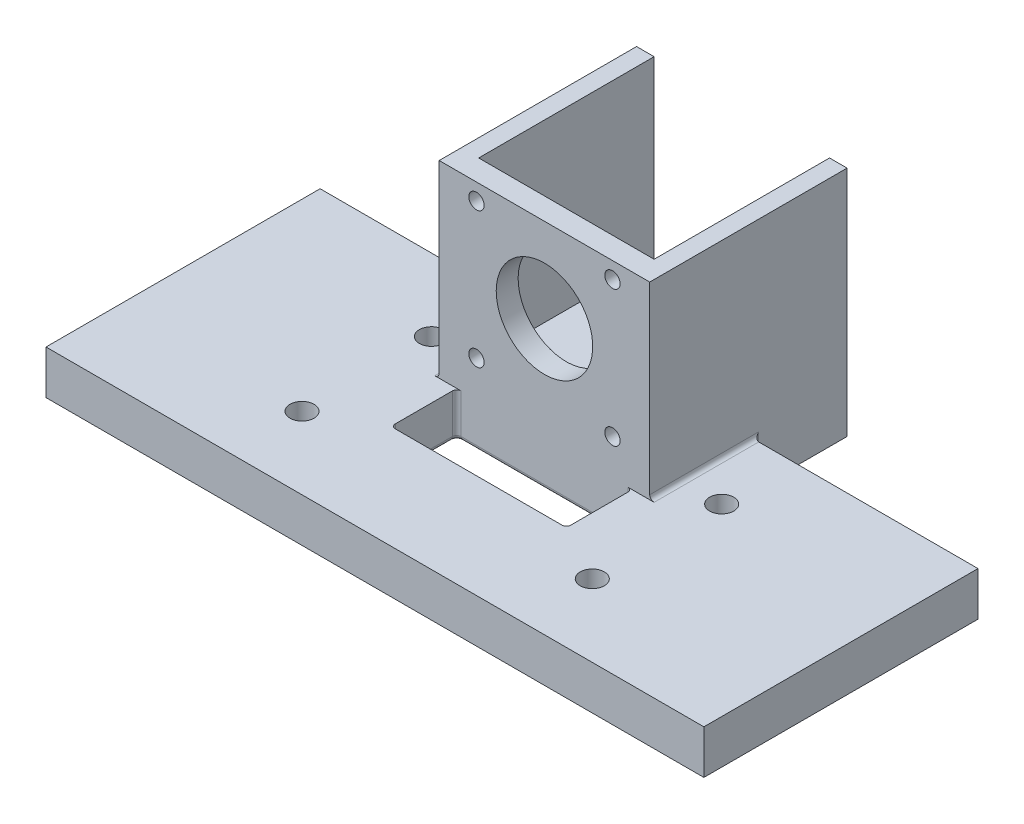
SolidWorks part; units mm, degrees
ref_plane "Front Plane" through (0, 0, 0) normal (0, 0, 1) x (1, 0, 0)
ref_plane "Top Plane" through (0, 0, 0) normal (0, 1, 0) x (1, 0, 0)
ref_plane "Right Plane" through (0, 0, 0) normal (1, 0, 0) x (0, 0, -1)
sketch "Sketch1" plane through (0, 0, 0) normal (0, 1, 0) x (1, 0, 0)
  line L0 (51, 62.5) -> (51, 83.65)
  line L1 (0, 0) -> (150, 0)
  line L2 (0, 0) -> (0, 62.5)
  line L4 (150, 0) -> (150, 62.5)
  line L5 (51, 83.65) -> (99, 83.65)
  line L6 (99, 83.65) -> (99, 62.5)
  line L8 (0, 62.5) -> (51, 62.5)
  line L9 (99, 62.5) -> (150, 62.5)
  line L10 (55, 38.65) -> (55, 23.65)
  line L11 (95, 38.65) -> (95, 23.65)
  line L14 (75, 83.65) -> (75, 38.65)
  line L15 (51, 83.65) -> (99, 83.65)
  line L17 (55, 23.65) -> (95, 23.65)
  line L22 (55, 38.65) -> (95, 38.65)
  circle A0 centre (108.0546, 46) radius 2.75
  circle A1 centre (41.8737, 46) radius 2.75
  circle A2 centre (41.8737, 16.5) radius 2.75
  circle A3 centre (108.0546, 16.5) radius 2.75
  dimension "D9" = 5.5
  dimension "D11" = 5.5
  dimension "D14" = 5.5
  dimension "D15" = 5.5
  dimension "D1" = 62.5
  dimension "D2" = 150
  dimension "D3" = 48
  dimension "D4" = 51
  dimension "D5" = 51
  dimension "D6" = 21.15
  dimension "D7" = 45
extrude "Boss-Extrude1" add sketch "Sketch1" along normal blind 10
sketch "Sketch3" plane through (0, 10, 0) normal (0, 1, 0) x (1, 0, 0)
  line L2 (95, 38.65) -> (95, 43.65)
  line L3 (55, 38.65) -> (95, 38.65)
  line L6 (95, 43.65) -> (55, 43.65)
  line L7 (95, 43.65) -> (95, 38.65)
  line L8 (95, 38.65) -> (55, 38.65)
  line L9 (55, 43.65) -> (55, 38.65)
  dimension "D3" = 40
extrude "Boss-Extrude2" add sketch "Sketch3" along normal blind 43 contours L6 L9 L3 L2
sketch "Sketch4" plane through (0, 0, -43.65) normal (0, 0, -1) x (-1, 0, 0)
  line L0 (-75, 53) -> (-75, 49.25)
  line L1 (-75, 49.25) -> (-75, 33.75)
  line L2 (-75, 22.75) -> (-75, 18.25)
  line L3 (-95, 53) -> (-55, 53) construction
  line L4 (-75, 49.25) -> (-90.5, 49.25)
  line L5 (-75, 49.25) -> (-59.5, 49.25)
  line L6 (-75, 18.25) -> (-90.5, 18.25)
  line L7 (-75, 18.25) -> (-59.5, 18.25)
  circle A0 centre (-90.5, 49.25) radius 1.75
  circle A1 centre (-59.5, 49.25) radius 1.75
  circle A2 centre (-75, 33.75) radius 11
  circle A3 centre (-90.5, 18.25) radius 1.75
  circle A4 centre (-59.5, 18.25) radius 1.75
  dimension "D4" = 3.5
  dimension "D5" = 3.5
  dimension "D7" = 22
  dimension "D9" = 3.5
  dimension "D10" = 3.5
  dimension "D1" = 3.75
  dimension "D2" = 15.5
  dimension "D3" = 15.5
  dimension "D6" = 15.5
  dimension "D8" = 4.5
extrude "Cut-Extrude1" cut sketch "Sketch4" against normal up to next
sketch "Sketch8" plane through (0, 10, 0) normal (0, 1, 0) x (1, 0, 0)
  line L2 (51, 83.65) -> (55, 83.65)
  line L7 (55, 38.65) -> (53.5, 38.65)
  line L8 (55, 43.65) -> (56.5, 43.65)
  line L12 (53.5, 38.65) -> (55, 38.65)
  line L14 (53.5, 83.65) -> (55, 83.65)
  line L16 (53.5, 38.65) -> (55, 38.65)
  line L18 (53.5, 83.65) -> (55, 83.65)
  line L19 (55, 38.65) -> (55, 83.65)
  line L20 (99, 83.65) -> (95, 83.65)
  line L21 (99, 83.65) -> (99, 38.65)
  line L22 (99, 38.65) -> (95, 38.65)
  line L23 (95, 83.65) -> (95, 38.65)
  line L24 (51, 83.65) -> (51, 38.65)
  line L25 (51, 38.65) -> (55, 38.65)
  line L26 (55, 83.65) -> (55, 38.65)
extrude "Boss-Extrude4" add sketch "Sketch8" along normal blind 43
sketch "Sketch11" plane through (0, 10, 0) normal (0, 1, 0) x (1, 0, 0)
  line L1 (55, 83.65) -> (95, 83.65)
  line L2 (55, 83.65) -> (55, 43.65)
  line L3 (55, 43.65) -> (95, 43.65)
  line L4 (95, 83.65) -> (95, 43.65)
extrude "Boss-Extrude15" add sketch "Sketch11" along normal blind 3
fillet "Fillet3" radius 1 8 edges at (95, 5, -38.65) (55, 5, -38.65) (55, 0, -31.15) (95, 0, -31.15) (75, 0, -38.65) (75, 0, -23.65) (55, 5, -23.65) (95, 5, -23.65)
fillet "Fillet6" radius 1 2 edges at (99, 10, -50.575) (51, 10, -50.575)
fillet "Fillet7" radius 1 2 edges at (99, 5.5, -62.5) (51, 5.5, -62.5)
